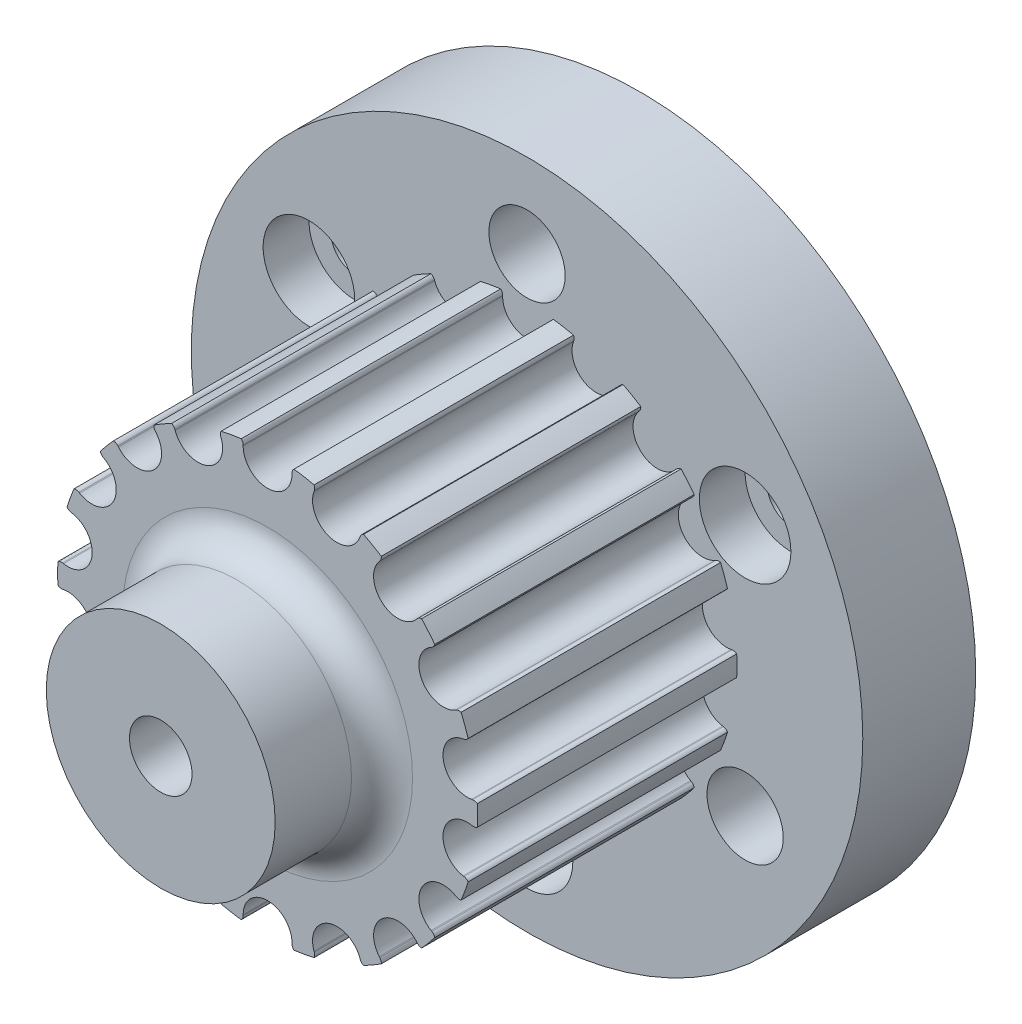
SolidWorks part; units mm, degrees
ref_plane "Front Plane" through (0, 0, 0) normal (0, 0, 1) x (1, 0, 0)
ref_plane "Top Plane" through (0, 0, 0) normal (0, 1, 0) x (1, 0, 0)
ref_plane "Right Plane" through (0, 0, 0) normal (1, 0, 0) x (0, 0, -1)
sketch "Sketch1" plane through (0, 0, 0) normal (0, 0, 1) x (1, 0, 0)
  circle A0 centre (0, 0) radius 22
  circle A1 centre (0, 0) radius 16.5 construction
  circle A2 centre (0, 16.5) radius 2.5
  circle A3 centre (14.2894, -8.25) radius 2.5
  circle A4 centre (-14.2894, -8.25) radius 2.5
  circle A5 centre (0, -16.5) radius 1.55
  circle A6 centre (-14.2894, 8.25) radius 1.55
  circle A7 centre (14.2894, 8.25) radius 1.55
  dimension "D1" = 44
  dimension "D2" = 33
  dimension "D3" = 5
  dimension "D5" = 3.1
  dimension "D4" = 3
  dimension "D6" = 3
sketch "Sketch3" plane through (0, 0, 0) normal (0, 0, 1) x (1, 0, 0)
  line L0 (3.0642, 13.0968) -> (3.0436, 13.0404)
  line L1 (6.0507, 11.946) -> (6.0712, 12.0024)
  line L2 (7.3588, 11.259) -> (7.3202, 11.213)
  line L3 (9.7715, 9.1561) -> (9.8101, 9.2021)
  line L4 (-1.6, 13.355) -> (-1.6, 13.295)
  line L5 (1.6, 13.295) -> (1.6, 13.355)
  line L6 (10.7658, 8.0631) -> (10.7138, 8.0331)
  line L7 (12.3138, 5.2619) -> (12.3658, 5.2919)
  line L8 (12.8743, 3.8948) -> (12.8152, 3.8843)
  line L9 (13.3709, 0.733) -> (13.4299, 0.7434)
  line L10 (13.4299, -0.7434) -> (13.3709, -0.733)
  line L11 (12.8152, -3.8843) -> (12.8743, -3.8948)
  line L12 (12.3658, -5.2919) -> (12.3138, -5.2619)
  line L13 (10.7138, -8.0331) -> (10.7658, -8.0631)
  line L14 (9.8101, -9.2021) -> (9.7715, -9.1561)
  line L15 (7.3202, -11.213) -> (7.3588, -11.259)
  line L16 (6.0712, -12.0024) -> (6.0507, -11.946)
  line L17 (3.0436, -13.0404) -> (3.0642, -13.0968)
  line L18 (1.6, -13.355) -> (1.6, -13.295)
  line L19 (-1.6, -13.295) -> (-1.6, -13.355)
  line L20 (-3.0642, -13.0968) -> (-3.0436, -13.0404)
  line L21 (-6.0507, -11.946) -> (-6.0712, -12.0024)
  line L22 (-7.3588, -11.259) -> (-7.3202, -11.213)
  line L23 (-9.7715, -9.1561) -> (-9.8101, -9.2021)
  line L24 (-10.7658, -8.0631) -> (-10.7138, -8.0331)
  line L25 (-12.3138, -5.2619) -> (-12.3658, -5.2919)
  line L26 (-12.8743, -3.8948) -> (-12.8152, -3.8843)
  line L27 (-13.3709, -0.733) -> (-13.4299, -0.7434)
  line L28 (-13.4299, 0.7434) -> (-13.3709, 0.733)
  line L29 (-12.8152, 3.8843) -> (-12.8743, 3.8948)
  line L30 (-12.3658, 5.2919) -> (-12.3138, 5.2619)
  line L31 (-10.7138, 8.0331) -> (-10.7658, 8.0631)
  line L32 (-9.8101, 9.2021) -> (-9.7715, 9.1561)
  line L33 (-7.3202, 11.213) -> (-7.3588, 11.259)
  line L34 (-6.0712, 12.0024) -> (-6.0507, 11.946)
  line L35 (-3.0436, 13.0404) -> (-3.0642, 13.0968)
  arc A2 (3.0455, 13.4136) -> (1.7259, 13.6463) centre (0, 0) ccw
  arc A3 (-1.7259, 13.6463) -> (-3.0455, 13.4136) centre (0, 0) ccw
  arc A4 (7.4496, 11.563) -> (6.2891, 12.233) centre (0, 0) ccw
  arc A5 (3.0455, 13.4136) -> (1.7259, 13.6463) centre (0, 0) ccw
  arc A6 (6.2891, 12.233) -> (6.0712, 12.0024) centre (6.4471, 11.8656) ccw
  arc A7 (6.2891, 12.233) -> (3.0455, 13.4136) centre (0, 0) ccw
  arc A8 (1.7259, 13.6463) -> (1.6, 13.355) centre (2, 13.355) ccw
  arc A9 (1.7259, 13.6463) -> (-1.7259, 13.6463) centre (0, 0) ccw
  arc A10 (-1.6, 13.355) -> (-1.7259, 13.6463) centre (-2, 13.355) ccw
  arc A11 (-1.6, 13.295) -> (1.6, 13.295) centre (0, 13.295) ccw
  arc A12 (3.0642, 13.0968) -> (3.0455, 13.4136) centre (2.6883, 13.2336) ccw
  arc A13 (3.0436, 13.0404) -> (6.0507, 11.946) centre (4.5472, 12.4932) ccw
  arc A14 (10.9551, 8.3178) -> (10.0938, 9.3443) centre (0, 0) ccw
  arc A15 (7.4496, 11.563) -> (6.2891, 12.233) centre (0, 0) ccw
  arc A16 (10.0938, 9.3443) -> (9.8101, 9.2021) centre (10.1165, 8.9449) ccw
  arc A17 (10.0938, 9.3443) -> (7.4496, 11.563) centre (0, 0) ccw
  arc A18 (7.3588, 11.259) -> (7.4496, 11.563) centre (7.0523, 11.5161) ccw
  arc A19 (7.3202, 11.213) -> (9.7715, 9.1561) centre (8.5459, 10.1846) ccw
  arc A20 (13.1393, 4.0693) -> (12.681, 5.3285) centre (0, 0) ccw
  arc A21 (10.9551, 8.3178) -> (10.0938, 9.3443) centre (0, 0) ccw
  arc A22 (12.681, 5.3285) -> (12.3658, 5.2919) centre (12.5658, 4.9454) ccw
  arc A23 (12.681, 5.3285) -> (10.9551, 8.3178) centre (0, 0) ccw
  arc A24 (10.7658, 8.0631) -> (10.9551, 8.3178) centre (10.5658, 8.4096) ccw
  arc A25 (10.7138, 8.0331) -> (12.3138, 5.2619) centre (11.5138, 6.6475) ccw
  arc A26 (13.7387, -0.67) -> (13.7387, 0.67) centre (0, 0) ccw
  arc A27 (13.1393, 4.0693) -> (12.681, 5.3285) centre (0, 0) ccw
  arc A28 (13.7387, 0.67) -> (13.4299, 0.7434) centre (13.4994, 0.3495) ccw
  arc A29 (13.7387, 0.67) -> (13.1393, 4.0693) centre (0, 0) ccw
  arc A30 (12.8743, 3.8948) -> (13.1393, 4.0693) centre (12.8048, 4.2887) ccw
  arc A31 (12.8152, 3.8843) -> (13.3709, 0.733) centre (13.093, 2.3087) ccw
  arc A32 (12.681, -5.3285) -> (13.1393, -4.0693) centre (0, 0) ccw
  arc A33 (13.7387, -0.67) -> (13.7387, 0.67) centre (0, 0) ccw
  arc A34 (13.1393, -4.0693) -> (12.8743, -3.8948) centre (12.8048, -4.2887) ccw
  arc A35 (13.1393, -4.0693) -> (13.7387, -0.67) centre (0, 0) ccw
  arc A36 (13.4299, -0.7434) -> (13.7387, -0.67) centre (13.4994, -0.3495) ccw
  arc A37 (13.3709, -0.733) -> (12.8152, -3.8843) centre (13.093, -2.3087) ccw
  arc A38 (10.0938, -9.3443) -> (10.9551, -8.3178) centre (0, 0) ccw
  arc A39 (12.681, -5.3285) -> (13.1393, -4.0693) centre (0, 0) ccw
  arc A40 (10.9551, -8.3178) -> (10.7658, -8.0631) centre (10.5658, -8.4096) ccw
  arc A41 (10.9551, -8.3178) -> (12.681, -5.3285) centre (0, 0) ccw
  arc A42 (12.3658, -5.2919) -> (12.681, -5.3285) centre (12.5658, -4.9454) ccw
  arc A43 (12.3138, -5.2619) -> (10.7138, -8.0331) centre (11.5138, -6.6475) ccw
  arc A44 (6.2891, -12.233) -> (7.4496, -11.563) centre (0, 0) ccw
  arc A45 (10.0938, -9.3443) -> (10.9551, -8.3178) centre (0, 0) ccw
  arc A46 (7.4496, -11.563) -> (7.3588, -11.259) centre (7.0523, -11.5161) ccw
  arc A47 (7.4496, -11.563) -> (10.0938, -9.3443) centre (0, 0) ccw
  arc A48 (9.8101, -9.2021) -> (10.0938, -9.3443) centre (10.1165, -8.9449) ccw
  arc A49 (9.7715, -9.1561) -> (7.3202, -11.213) centre (8.5459, -10.1846) ccw
  arc A50 (1.7259, -13.6463) -> (3.0455, -13.4136) centre (0, 0) ccw
  arc A51 (6.2891, -12.233) -> (7.4496, -11.563) centre (0, 0) ccw
  arc A52 (3.0455, -13.4136) -> (3.0642, -13.0968) centre (2.6883, -13.2336) ccw
  arc A53 (3.0455, -13.4136) -> (6.2891, -12.233) centre (0, 0) ccw
  arc A54 (6.0712, -12.0024) -> (6.2891, -12.233) centre (6.4471, -11.8656) ccw
  arc A55 (6.0507, -11.946) -> (3.0436, -13.0404) centre (4.5472, -12.4932) ccw
  arc A56 (-3.0455, -13.4136) -> (-1.7259, -13.6463) centre (0, 0) ccw
  arc A57 (1.7259, -13.6463) -> (3.0455, -13.4136) centre (0, 0) ccw
  arc A58 (-1.7259, -13.6463) -> (-1.6, -13.355) centre (-2, -13.355) ccw
  arc A59 (-1.7259, -13.6463) -> (1.7259, -13.6463) centre (0, 0) ccw
  arc A60 (1.6, -13.355) -> (1.7259, -13.6463) centre (2, -13.355) ccw
  arc A61 (1.6, -13.295) -> (-1.6, -13.295) centre (0, -13.295) ccw
  arc A62 (-7.4496, -11.563) -> (-6.2891, -12.233) centre (0, 0) ccw
  arc A63 (-3.0455, -13.4136) -> (-1.7259, -13.6463) centre (0, 0) ccw
  arc A64 (-6.2891, -12.233) -> (-6.0712, -12.0024) centre (-6.4471, -11.8656) ccw
  arc A65 (-6.2891, -12.233) -> (-3.0455, -13.4136) centre (0, 0) ccw
  arc A66 (-3.0642, -13.0968) -> (-3.0455, -13.4136) centre (-2.6883, -13.2336) ccw
  arc A67 (-3.0436, -13.0404) -> (-6.0507, -11.946) centre (-4.5472, -12.4932) ccw
  arc A68 (-10.9551, -8.3178) -> (-10.0938, -9.3443) centre (0, 0) ccw
  arc A69 (-7.4496, -11.563) -> (-6.2891, -12.233) centre (0, 0) ccw
  arc A70 (-10.0938, -9.3443) -> (-9.8101, -9.2021) centre (-10.1165, -8.9449) ccw
  arc A71 (-10.0938, -9.3443) -> (-7.4496, -11.563) centre (0, 0) ccw
  arc A72 (-7.3588, -11.259) -> (-7.4496, -11.563) centre (-7.0523, -11.5161) ccw
  arc A73 (-7.3202, -11.213) -> (-9.7715, -9.1561) centre (-8.5459, -10.1846) ccw
  arc A74 (-13.1393, -4.0693) -> (-12.681, -5.3285) centre (0, 0) ccw
  arc A75 (-10.9551, -8.3178) -> (-10.0938, -9.3443) centre (0, 0) ccw
  arc A76 (-12.681, -5.3285) -> (-12.3658, -5.2919) centre (-12.5658, -4.9454) ccw
  arc A77 (-12.681, -5.3285) -> (-10.9551, -8.3178) centre (0, 0) ccw
  arc A78 (-10.7658, -8.0631) -> (-10.9551, -8.3178) centre (-10.5658, -8.4096) ccw
  arc A79 (-10.7138, -8.0331) -> (-12.3138, -5.2619) centre (-11.5138, -6.6475) ccw
  arc A80 (-13.7387, 0.67) -> (-13.7387, -0.67) centre (0, 0) ccw
  arc A81 (-13.1393, -4.0693) -> (-12.681, -5.3285) centre (0, 0) ccw
  arc A82 (-13.7387, -0.67) -> (-13.4299, -0.7434) centre (-13.4994, -0.3495) ccw
  arc A83 (-13.7387, -0.67) -> (-13.1393, -4.0693) centre (0, 0) ccw
  arc A84 (-12.8743, -3.8948) -> (-13.1393, -4.0693) centre (-12.8048, -4.2887) ccw
  arc A85 (-12.8152, -3.8843) -> (-13.3709, -0.733) centre (-13.093, -2.3087) ccw
  arc A86 (-12.681, 5.3285) -> (-13.1393, 4.0693) centre (0, 0) ccw
  arc A87 (-13.7387, 0.67) -> (-13.7387, -0.67) centre (0, 0) ccw
  arc A88 (-13.1393, 4.0693) -> (-12.8743, 3.8948) centre (-12.8048, 4.2887) ccw
  arc A89 (-13.1393, 4.0693) -> (-13.7387, 0.67) centre (0, 0) ccw
  arc A90 (-13.4299, 0.7434) -> (-13.7387, 0.67) centre (-13.4994, 0.3495) ccw
  arc A91 (-13.3709, 0.733) -> (-12.8152, 3.8843) centre (-13.093, 2.3087) ccw
  arc A92 (-10.0938, 9.3443) -> (-10.9551, 8.3178) centre (0, 0) ccw
  arc A93 (-12.681, 5.3285) -> (-13.1393, 4.0693) centre (0, 0) ccw
  arc A94 (-10.9551, 8.3178) -> (-10.7658, 8.0631) centre (-10.5658, 8.4096) ccw
  arc A95 (-10.9551, 8.3178) -> (-12.681, 5.3285) centre (0, 0) ccw
  arc A96 (-12.3658, 5.2919) -> (-12.681, 5.3285) centre (-12.5658, 4.9454) ccw
  arc A97 (-12.3138, 5.2619) -> (-10.7138, 8.0331) centre (-11.5138, 6.6475) ccw
  arc A98 (-6.2891, 12.233) -> (-7.4496, 11.563) centre (0, 0) ccw
  arc A99 (-10.0938, 9.3443) -> (-10.9551, 8.3178) centre (0, 0) ccw
  arc A100 (-7.4496, 11.563) -> (-7.3588, 11.259) centre (-7.0523, 11.5161) ccw
  arc A101 (-7.4496, 11.563) -> (-10.0938, 9.3443) centre (0, 0) ccw
  arc A102 (-9.8101, 9.2021) -> (-10.0938, 9.3443) centre (-10.1165, 8.9449) ccw
  arc A103 (-9.7715, 9.1561) -> (-7.3202, 11.213) centre (-8.5459, 10.1846) ccw
  arc A104 (-1.7259, 13.6463) -> (-3.0455, 13.4136) centre (0, 0) ccw
  arc A105 (-6.2891, 12.233) -> (-7.4496, 11.563) centre (0, 0) ccw
  arc A106 (-3.0455, 13.4136) -> (-3.0642, 13.0968) centre (-2.6883, 13.2336) ccw
  arc A107 (-3.0455, 13.4136) -> (-6.2891, 12.233) centre (0, 0) ccw
  arc A108 (-6.0712, 12.0024) -> (-6.2891, 12.233) centre (-6.4471, 11.8656) ccw
  arc A109 (-6.0507, 11.946) -> (-3.0436, 13.0404) centre (-4.5472, 12.4932) ccw
  point P239 (0, 0)
  dimension "D1" = 18
extrude "Boss-Extrude1" add sketch "Sketch3" along normal blind 24.4 contours A109 L34 A108 A98 A100 L33 A103 L32 A102 A92 A94 L31 A97 L30 A96 A86 A88 L29 A91 L28 A90 A80 A82 L27 A85 L26 A84 A74 A76 L25 A79 L24 A78 A68 A70 L23 A73 L22 A72 A62 A64 L21 A67 L20 A66 A56 A58 L19 A61 L18 A60
extrude "Boss-Extrude2" add sketch "Sketch1" along normal blind 7.4
sketch "Sketch4" plane through (0, 0, 7.4) normal (0, 0, 1) x (1, 0, 0)
  circle A0 centre (0, -16.5) radius 3
  circle A1 centre (-14.2894, 8.25) radius 3
  circle A2 centre (14.2894, 8.25) radius 3
  point P9 (0, 0)
  dimension "D1" = 6
  dimension "D2" = 3
extrude "Cut-Extrude1" cut sketch "Sketch4" against normal blind 3
sketch "Sketch5" plane through (0, 0, 24.4) normal (0, 0, 1) x (1, 0, 0)
  circle A0 centre (0, 0) radius 7.5
  dimension "D1" = 15
extrude "Boss-Extrude3" add sketch "Sketch5" along normal blind 7
fillet "Fillet1" radius 2 1 edges at (7.5, 0, 24.4)
sketch "Sketch6" plane through (0, 0, 31.4) normal (0, 0, 1) x (1, 0, 0)
  circle A0 centre (0, 0) radius 2.05
  dimension "D1" = 4.1
extrude "Cut-Extrude2" cut sketch "Sketch6" against normal blind 8
equation "\"NT\"= 18"
equation "\"Pitch\"= 5mm"
equation "\"PD\"= \"NT\" * \"Pitch\" / 3.14159"
equation "\"U\"= 0.5715mm"
equation "\"OD\"= \"PD\" - ( 2 * \"U\" )"
equation "\"AS\"= 360deg / \"NT\""
